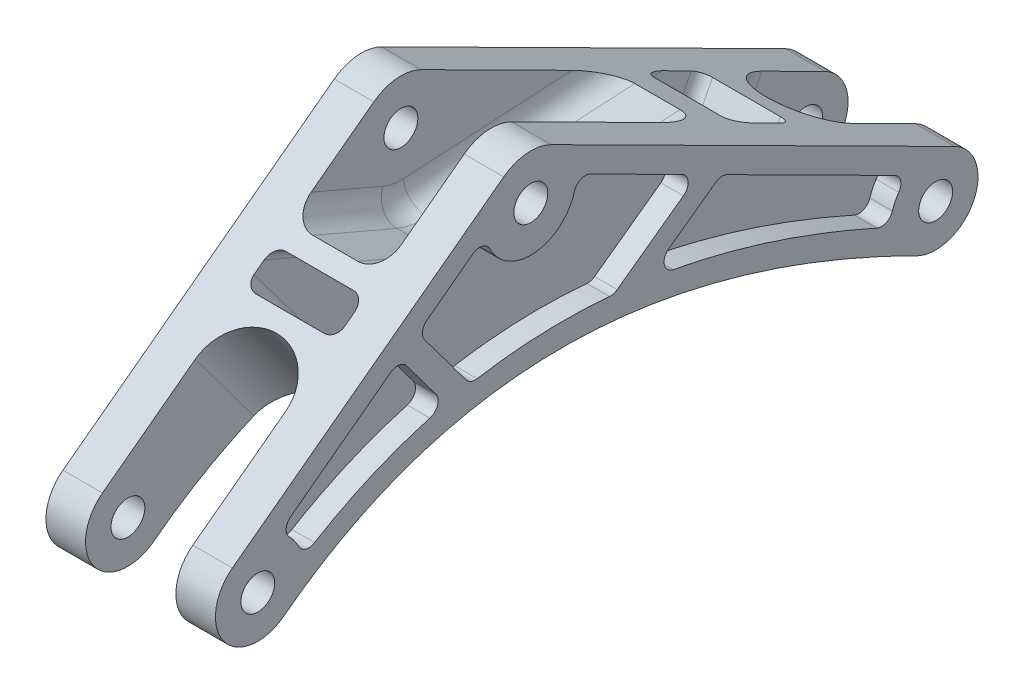
SolidWorks part; units mm, degrees
ref_plane "前视基准面" through (0, 0, 0) normal (0, 0, 1) x (1, 0, 0)
ref_plane "上视基准面" through (0, 0, 0) normal (0, 1, 0) x (1, 0, 0)
ref_plane "右视基准面" through (0, 0, 0) normal (1, 0, 0) x (0, 0, -1)
sketch "草图1" plane through (0, 0, 0) normal (1, 0, 0) x (0, 0, -1)
  line L0 (0, 0) -> (-60, 0) construction
  line L1 (-60, 0) -> (-35.8333, 17.7756) construction
  line L2 (-35.8333, 17.7756) -> (0, 0) construction
  line L3 (-62.247, 3.0022) -> (-38.2302, 20.978)
  line L4 (-34.0334, 21.3478) -> (1.6874, 3.3489)
  line L9 (-57.7207, -2.9778) -> (-35.8333, 13.7756) construction
  line L10 (-35.8333, 13.7756) -> (-1.6811, -3.3521) construction
  circle A0 centre (0, 0) radius 1.5
  circle A1 centre (-35.8333, 17.7756) radius 1.5
  circle A2 centre (-60, 0) radius 1.5
  arc A3 (-62.247, 3.0022) -> (-57.7207, -2.9778) centre (-60, 0) ccw
  arc A4 (-1.6811, -3.3521) -> (1.6874, 3.3489) centre (0, 0) ccw
  circle A5 centre (-35.8333, 17.7756) radius 4 construction
  arc A6 (-38.2302, 20.978) -> (-34.0334, 21.3478) centre (-35.8333, 17.7756) cw
  spline S0 degree 1 poles (-57.7207, -2.9778) (-35.8333, 13.7756) knots 0 0 1 1 construction
  spline S4 degree 2 poles (-57.7207, -2.9778) (-35.8333, 13.7756) (-1.6811, -3.3521) knots 0 0 0 1 1 1
  dimension "D4" = 3
  dimension "D5" = 7.5
  dimension "D6" = 8
  dimension "D1" = 60
  dimension "D2" = 30
  dimension "D3" = 40
extrude "凸台-拉伸1" add sketch "草图1" along normal mid plane 15
sketch "草图3" plane through (0, 3.3489, -1.6874) normal (0, 0.893, -0.45) x (1, 0, 0)
  line L0 (0, 3.75) -> (0, -6.25) construction
  line L1 (7.5, 3.75) -> (-7.5, 3.75) construction
  line L2 (4, -6.25) -> (4, 3.75)
  line L3 (4, 3.75) -> (-4, 3.75)
  line L4 (-4, 3.75) -> (-4, -6.25)
  arc A0 (-4, -6.25) -> (4, -6.25) centre (0, -6.25) ccw
  dimension "D2" = 8
  dimension "D1" = 10
extrude "切除-拉伸1" cut sketch "草图3" against normal through all
sketch "草图4" plane through (0, 31.7856, 23.7904) normal (0, 0.8006, 0.5992) x (1, 0, 0)
  line L0 (0, -51.7854) -> (0, -37.7854) construction
  line L1 (-7.5, -51.7854) -> (7.5, -51.7854) construction
  line L2 (4, -37.7854) -> (4, -51.7854)
  line L3 (4, -51.7854) -> (-4, -51.7854)
  line L4 (-4, -51.7854) -> (-4, -37.7854)
  arc A0 (4, -37.7854) -> (-4, -37.7854) centre (0, -37.7854) ccw
  dimension "D2" = 8
  dimension "D1" = 14
extrude "切除-拉伸2" cut sketch "草图4" against normal through all
sketch "草图5" plane through (0, 0, 0) normal (1, 0, 0) x (0, 0, -1)
  line L0 (-35.4924, 11.7853) -> (-17.1298, 12.8304)
  line L1 (1.6874, 3.3489) -> (-34.0334, 21.3478) construction
  line L2 (-38.1957, 12.2602) -> (-45.6257, 15.4427)
  line L3 (-38.2302, 20.978) -> (-62.247, 3.0022) construction
  line L4 (-17.1298, 12.8304) -> (-34.0334, 21.3478)
  line L5 (-38.2302, 20.978) -> (-45.6257, 15.4427)
  arc A0 (-38.1957, 12.2602) -> (-35.4924, 11.7853) centre (-35.8333, 17.7756) ccw
  arc A1 (-34.0334, 21.3478) -> (-38.2302, 20.978) centre (-35.8333, 17.7756) ccw construction
  arc A2 (-34.0334, 21.3478) -> (-38.2302, 20.978) centre (-35.8333, 17.7756) ccw
  dimension "D1" = 12
  dimension "D2" = 60
  dimension "D3" = 30
extrude "切除-拉伸3" cut sketch "草图5" against normal mid plane 8
fillet "圆角1" radius 2 6 edges at (4, 12.3079, 26.3111) (4, 11.8661, 36.8716) (-4, 13.8515, 41.9107) (-4, 11.8661, 36.8716) (4, 13.8515, 41.9107) (-4, 12.3079, 26.3111)
sketch "草图6" plane through (0, 0, 0) normal (1, 0, 0) x (0, 0, -1)
  line L0 (-50.8386, 11.541) -> (-54.041, 9.1441) construction
  line L1 (-50.8386, 11.541) -> (-54.041, 9.1441) construction
  line L2 (-38.1957, 12.2602) -> (-45.6257, 15.4427) construction
  line L3 (-38.1957, 12.2602) -> (-45.6257, 15.4427) construction
  line L4 (-3.8941, 6.1613) -> (-7.4662, 7.9612) construction
  line L5 (-35.4924, 11.7853) -> (-17.1298, 12.8304) construction
  line L6 (-3.8941, 6.1613) -> (-7.4662, 7.9612) construction
  line L7 (-35.4924, 11.7853) -> (-17.1298, 12.8304) construction
  line L8 (-49.6378, 12.4398) -> (-43.3628, 4.0561)
  line L9 (-38.2302, 20.978) -> (-62.247, 3.0022) construction
  line L10 (-35.4071, 10.2877) -> (-17.0446, 11.3329)
  line L11 (-38.7863, 10.8814) -> (-46.2163, 14.0638)
  line L12 (-46.2163, 14.0638) -> (-47.0124, 14.4048)
  line L13 (-47.0124, 14.4048) -> (-49.6378, 12.4398)
  line L14 (-17.0446, 11.3329) -> (-14.4507, 11.4805)
  line L15 (1.6874, 3.3489) -> (-34.0334, 21.3478) construction
  line L16 (-14.4507, 11.4805) -> (-9.2523, 8.8612)
  line L17 (-9.2523, 8.8612) -> (-12.9613, 1.5003)
  line L18 (-7.4662, 7.9612) -> (-11.9233, -0.8844) construction
  arc A0 (-38.1957, 12.2602) -> (-35.4924, 11.7853) centre (-35.8333, 17.7756) ccw construction
  arc A1 (-38.1957, 12.2602) -> (-35.4924, 11.7853) centre (-35.8333, 17.7756) ccw construction
  arc A2 (-38.7863, 10.8814) -> (-35.4071, 10.2877) centre (-35.8333, 17.7756) ccw
  parabola Q0 (-57.7207, -2.9778) -> (-1.6811, -3.3521) focus (-40.457, -15.0824) apex (-46.9825, 2.9441) construction
  parabola Q1 (-57.7207, -2.9778) -> (-1.6811, -3.3521) focus (-40.457, -15.0824) apex (-46.9825, 2.9441) construction
  parabola Q3 (-57.7207, -2.9778) -> (-1.6811, -3.3521) focus (-40.457, -15.0824) apex (-46.9825, 2.9441) construction
  parabola Q4 (-43.3628, 4.0561) -> (-12.9613, 1.5003) focus (-40.457, -15.0824) apex (-46.9825, 2.9441)
  dimension "D1" = 1.5
  dimension "D3" = 2
  dimension "D2" = 1.5
extrude "切除-拉伸4" cut sketch "草图6" against normal mid plane 8
fillet "圆角2" radius 1 10 edges at (4, 10.8841, 24.9289) (4, 10.3887, 37.1311) (-4, 10.8841, 24.9289) (-4, 10.3887, 37.1311) (-4, 5.1807, 11.1068) (4, 5.1807, 11.1068) (-4, 8.2479, 46.5003) (4, 12.6431, 42.8993) (-4, 12.6431, 42.8993) (4, 8.2479, 46.5003)
sketch "草图7" plane through (7.5, 0, 0) normal (1, 0, 0) x (0, 0, -1)
  line L0 (-20.9955, 12.5387) -> (-31.8398, 18.0029)
  line L1 (-47.4334, 11.5916) -> (-58.169, 3.5563)
  line L2 (-28.4914, 7.095) -> (-20.9955, 12.5387)
  line L3 (-25.5631, 6.7498) -> (-18.9861, 11.5263)
  line L4 (0.7875, 1.5628) -> (-34.9334, 19.5617)
  line L5 (-37.0318, 19.3768) -> (-61.0486, 1.401)
  line L6 (-2.4247, 3.1813) -> (-18.9861, 11.5263)
  line L7 (-39.8051, 17.3011) -> (-45.8322, 12.79)
  line L8 (-41.1843, 6.5801) -> (-45.8322, 12.79)
  line L9 (-47.4334, 11.5916) -> (-43.3397, 6.1221)
  arc A3 (-39.8051, 17.3011) -> (-31.8398, 18.0029) centre (-35.8333, 17.7756) ccw
  arc A4 (-56.0523, 0.6445) -> (-58.169, 3.5563) centre (-60, 0) ccw
  arc A5 (-2.4247, 3.1813) -> (-4, -0.013) centre (0, 0) ccw
  arc A6 (-0.7845, -1.5643) -> (0.7875, 1.5628) centre (0, 0) ccw
  arc A7 (-34.9334, 19.5617) -> (-37.0318, 19.3768) centre (-35.8333, 17.7756) ccw
  arc A8 (-61.0486, 1.401) -> (-58.9363, -1.3896) centre (-60, 0) ccw
  spline S0 degree 3 poles (-5388.1712, 8363.8054) (629.3843, -2376.2157) (-282.3697, -115.7611) (-51.3145, 3.3189) (-49.5696, 4.1183) (-47.7594, 4.7953) (-46.5379, 5.2189) (-45.9198, 5.4166) (-42.8263, 6.3257) (-40.3144, 6.8078) (-36.4965, 7.2002) (-35.2154, 7.2758) (-33.282, 7.3103) (-32.6341, 7.3086) (-31.3435, 7.2798) (-30.7004, 7.2527) (-27.4961, 7.0582) (-24.967, 6.7137) (-19.9636, 5.7225) (-17.4895, 5.0755) (-13.8123, 3.9181) (-12.5916, 3.5006) (-10.1767, 2.6147) (-8.9802, 2.1456) (199.3261, -84.3044) (107.2008, -880.228) (4471.0383, 8895.7321) knots -12.530814 -12.530814 -12.530814 -12.530814 0.125 0.125 0.1875 0.21875 0.21875 0.25 0.25 0.375 0.375 0.4375 0.4375 0.46875 0.46875 0.5 0.5 0.625 0.625 0.75 0.75 0.8125 0.8125 0.875 0.875 11.784072 11.784072 11.784072 11.784072 only from (-58.9363, -1.3896) to (-0.7845, -1.5643)
  spline S1 degree 3 poles (-56.0523, 0.6445) (-54.8835, 1.401) (-53.6832, 2.0982) (-51.3145, 3.3189) (-49.5696, 4.1183) (-47.7594, 4.7953) (-46.5379, 5.2189) (-45.9198, 5.4166) (-44.6498, 5.7898) (-43.996, 5.9642) (-43.3397, 6.1221) knots 0.05712 0.05712 0.05712 0.05712 0.125 0.125 0.1875 0.21875 0.21875 0.25 0.25 0.282895 0.282895 0.282895 0.282895
  spline S2 degree 3 poles (-25.5631, 6.7498) (-24.5256, 6.5998) (-23.4931, 6.4217) (-19.9636, 5.7225) (-17.4895, 5.0755) (-13.8123, 3.9181) (-12.5916, 3.5006) (-10.1767, 2.6147) (-8.9802, 2.1456) (-6.518, 1.1238) (-5.2539, 0.5675) (-4, -0.013) knots 0.573643 0.573643 0.573643 0.573643 0.625 0.625 0.75 0.75 0.8125 0.8125 0.875 0.875 0.942181 0.942181 0.942181 0.942181
  spline S3 degree 3 poles (-41.1843, 6.5801) (-40.0529, 6.7894) (-38.9144, 6.9517) (-36.4965, 7.2002) (-35.2154, 7.2758) (-33.282, 7.3103) (-32.6341, 7.3086) (-31.3435, 7.2798) (-30.7004, 7.2527) (-29.5354, 7.182) (-29.0127, 7.1423) (-28.4914, 7.095) knots 0.318755 0.318755 0.318755 0.318755 0.375 0.375 0.4375 0.4375 0.46875 0.46875 0.5 0.5 0.525559 0.525559 0.525559 0.525559
  dimension "D2" = 8
  dimension "D3" = 2
  dimension "D4" = 2
  dimension "D1" = 2
extrude "切除-拉伸5" cut sketch "草图7" against normal blind 2
fillet "圆角3" radius 1 14 edges at (6.5, 17.3011, 39.8051) (6.5, 12.79, 45.8322) (6.5, 12.5387, 20.9955) (6.5, 18.0029, 31.8398) (6.5, 3.1813, 2.4247) (6.5, 11.5263, 18.9861) (6.5, 3.5563, 58.169) (6.5, 11.5916, 47.4334)
mirror "镜向1" about plane through (0, 0, 0) normal (1, 0, 0) of "切除-拉伸5", "圆角3"
